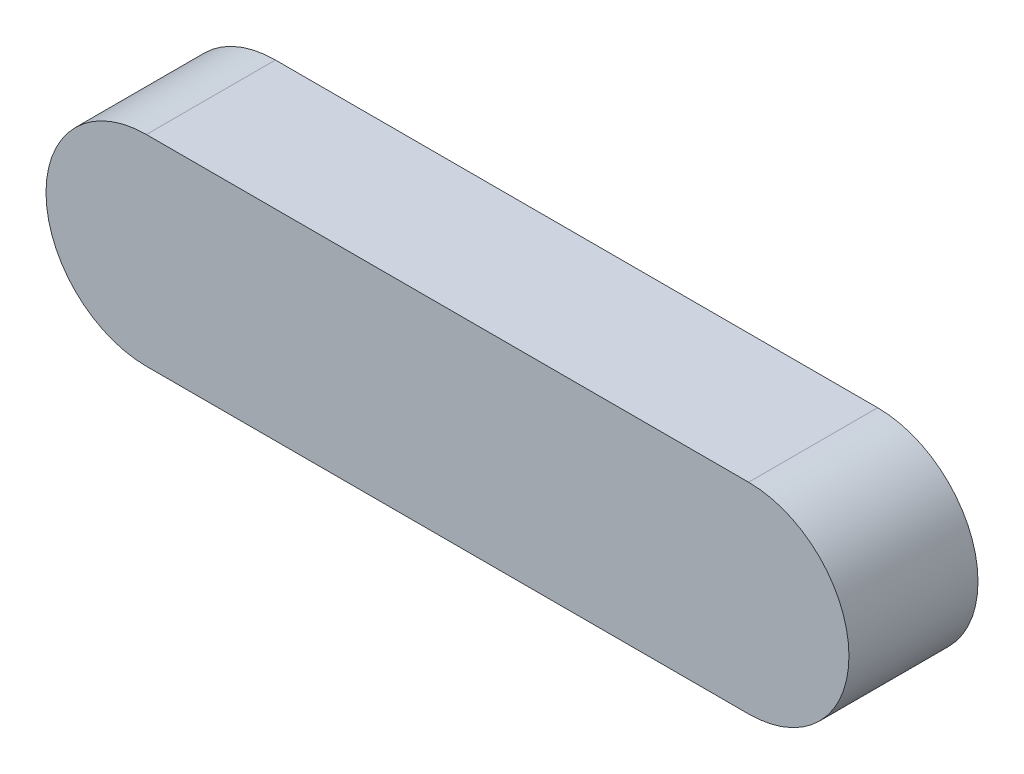
SolidWorks part; units mm, degrees
material "Plain Carbon Steel"
ref_plane "Front Plane" through (0, 0, 0) normal (0, 0, 1) x (1, 0, 0)
ref_plane "Top Plane" through (0, 0, 0) normal (0, 1, 0) x (1, 0, 0)
ref_plane "Right Plane" through (0, 0, 0) normal (1, 0, 0) x (0, 0, -1)
sketch "Sketch1" plane through (0, 0, 0) normal (0, 0, 1) x (1, 0, 0)
  line L0 (-21, 0) -> (21, 0) construction
  line L1 (-21, 7) -> (21, 7)
  line L2 (-21, -7) -> (21, -7)
  arc A0 (-21, 7) -> (-21, -7) centre (-21, 0) ccw
  arc A1 (21, -7) -> (21, 7) centre (21, 0) ccw
  point P2 (0, 0)
  dimension "D2" = 56
  dimension "D1" = 14
extrude "Extrude1" add sketch "Sketch1" along normal blind 9
other "Freeze***"
